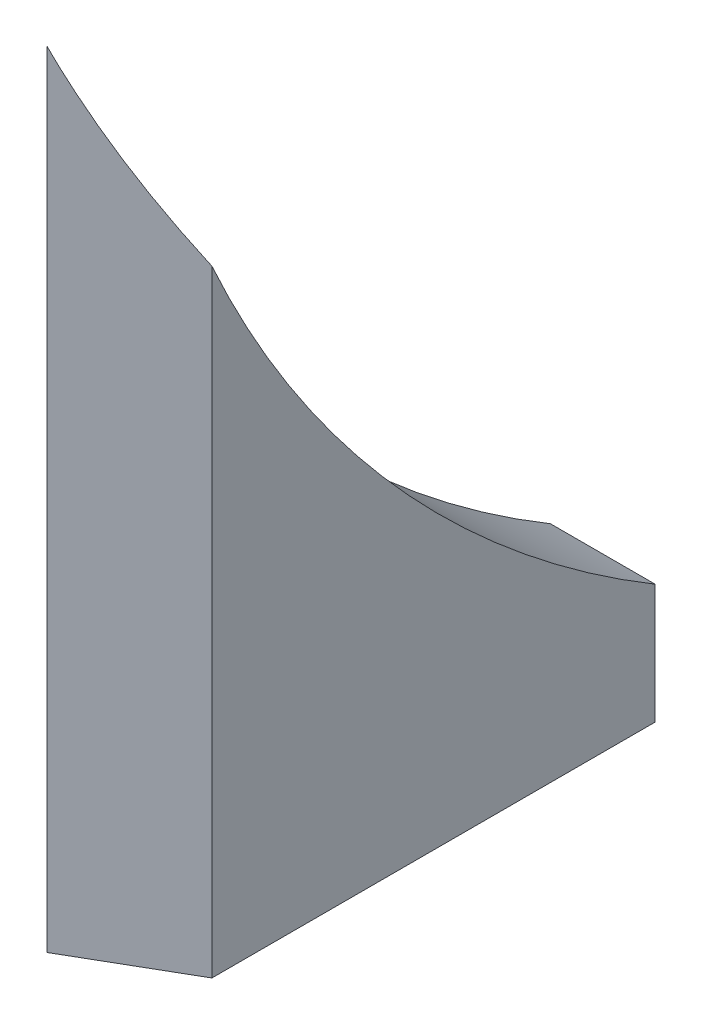
SolidWorks part; units mm, degrees
ref_plane "Front Plane" through (0, 0, 0) normal (0, 0, 1) x (1, 0, 0)
ref_plane "Top Plane" through (0, 0, 0) normal (0, 1, 0) x (1, 0, 0)
ref_plane "Right Plane" through (0, 0, 0) normal (1, 0, 0) x (0, 0, -1)
sketch "Sketch1" plane through (0, 0, 0) normal (1, 0, 0) x (0, 0, -1)
  line L0 (-11.8671, 22.332) -> (-11.8671, -7.668)
  line L1 (-11.8671, -7.668) -> (18.1329, -7.668)
  arc A0 (-11.8671, 22.332) -> (18.1329, -7.668) centre (29.2351, 33.4343) ccw
  dimension "D1" = 30
  dimension "D2" = 30
extrude "Boss-Extrude1" add sketch "Sketch1" along normal blind 4
sketch "Sketch2" plane through (4, 0, 0) normal (1, 0, 0) x (0, 0, -1)
  line L0 (-11.8671, 22.332) -> (-11.8671, -7.668) construction
  line L1 (18.1329, -7.668) -> (7.3829, -7.668)
  line L2 (18.1329, -7.668) -> (18.1329, 12.6592)
  line L3 (18.1329, 12.6592) -> (7.3829, 12.6592)
  line L4 (7.3829, -7.668) -> (7.3829, 12.6592)
  dimension "D1" = 19.25
extrude "Cut-Extrude1" cut sketch "Sketch2" against normal blind 4
sketch "Sketch3" plane through (0, -7.668, 0) normal (0, -1, 0) x (1, 0, 0)
  line L0 (0, 11.8671) -> (4, 9.5577)
  line L1 (4, 11.8671) -> (4, -7.3829) construction
  line L2 (4, 9.5577) -> (4, 11.8671)
  line L3 (4, 11.8671) -> (0, 11.8671)
  dimension "D1" = 30
extrude "Cut-Extrude2" cut sketch "Sketch3" against normal blind 50.8
